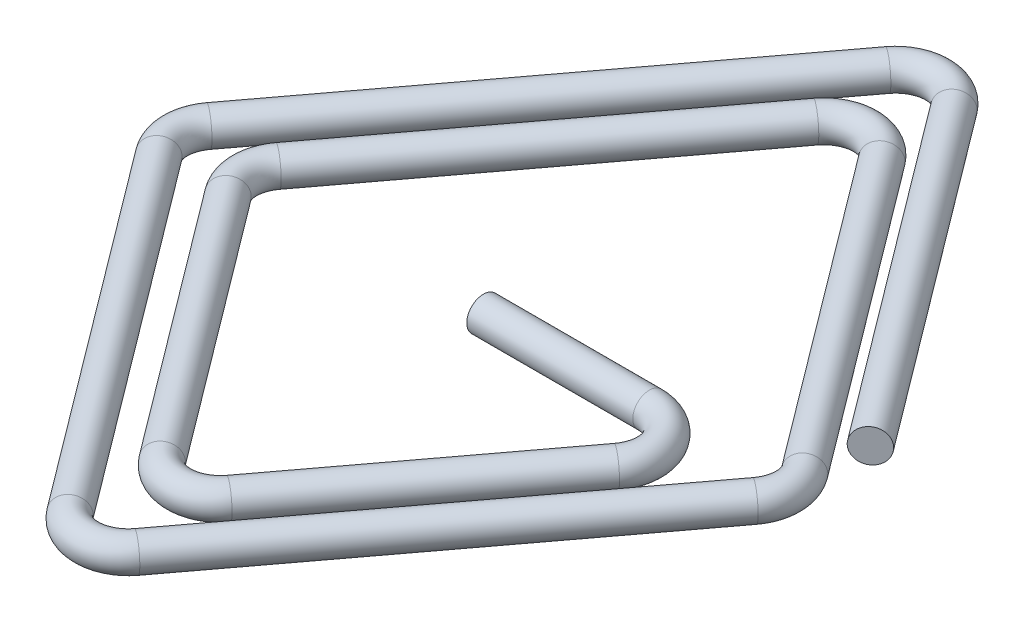
SolidWorks part; units mm, degrees
ref_plane "Спереди" through (0, 0, 0) normal (0, 0, 1) x (1, 0, 0)
ref_plane "Сверху" through (0, 0, 0) normal (0, 1, 0) x (1, 0, 0)
ref_plane "Справа" through (0, 0, 0) normal (1, 0, 0) x (0, 0, -1)
sketch "Эскиз1" plane through (0, 0, 0) normal (0, 1, 0) x (1, 0, 0)
  line L0 (0, 0) -> (9, 0) construction
  line L1 (9, 0) -> (0, -12) construction
  line L2 (0, -12) -> (-9, 0) construction
  line L3 (-9, 0) -> (0, 12) construction
  line L4 (11.45, -0.0667) -> (0, -15.3333) construction
  line L5 (0, -15.3333) -> (-11.5, 0) construction
  line L6 (-11.5, 0) -> (-1.6, 13.2) construction
  line L7 (0, 12) -> (1.2, 13.6) construction
  line L8 (1.2, 13.6) -> (11.45, -0.0667) construction
  line L9 (10.2, 1.6) -> (9, 0) construction
  line L10 (10.6, -1.2) -> (0, -15.3333) construction
  line L12 (2.4, 14.5) -> (12.65, 0.8333) construction
  line L13 (-1.6, 13.2) -> (0.8875, 16.5167) construction
  line L14 (0.8875, 16.5167) -> (2.4, 14.5) construction
  point P16 (11.1375, 2.85)
  dimension "D1" = 12
  dimension "D2" = 9
  dimension "D3" = 2
  dimension "D4" = 2
  dimension "D5" = 1.5
sketch "Эскиз2" plane through (0, 0, 0) normal (0, 1, 0) x (1, 0, 0)
  line L0 (11.1375, 2.85) -> (2.0875, 14.9167)
  line L1 (-0.3125, 14.9167) -> (-10.825, 0.9)
  line L2 (-10.825, -0.9) -> (-1.2, -13.7333)
  line L3 (1.2, -13.7333) -> (10.775, -0.9667)
  line L4 (10.775, 0.8333) -> (2.4, 12)
  line L5 (0, 12) -> (-8.325, 0.9)
  line L6 (-8.325, -0.9) -> (-1.2, -10.4)
  line L7 (1.2, -10.4) -> (7.2, -2.4)
  line L8 (6, 0) -> (0, 0)
  arc A0 (10.775, -0.9667) -> (10.775, 0.8333) centre (9.575, -0.0667) ccw
  arc A1 (-1.2, -10.4) -> (1.2, -10.4) centre (0, -9.5) ccw
  arc A2 (-8.325, -0.9) -> (-8.325, 0.9) centre (-7.125, 0) cw
  arc A3 (2.4, 12) -> (0, 12) centre (1.2, 11.1) ccw
  arc A4 (2.0875, 14.9167) -> (-0.3125, 14.9167) centre (0.8875, 14.0167) ccw
  arc A5 (-10.825, 0.9) -> (-10.825, -0.9) centre (-9.625, 0) ccw
  arc A6 (-1.2, -13.7333) -> (1.2, -13.7333) centre (0, -12.8333) ccw
  arc A7 (6, 0) -> (7.2, -2.4) centre (6, -1.5) cw
  point P22 (11.45, -0.0667)
  point P25 (0, -12)
  point P28 (-9, 0)
  point P31 (1.2, 13.6)
  point P34 (0.8875, 16.5167)
  point P37 (-11.5, 0)
  point P40 (0, -15.3333)
  point P43 (9, 0)
  dimension "D1" = 1.5
  dimension "D2" = 1.5
  dimension "D3" = 1.5
ref_plane "Плоскость3" through (11.1375, 0, -2.85) normal (0.6, 0, 0.8) x (0.8, 0, -0.6)
sketch "Эскиз3" plane through (11.1375, 0, -2.85) normal (0.6, 0, 0.8) x (0.8, 0, -0.6)
  circle A0 centre (0, 0) radius 0.6
  dimension "D1" = 1.2
sweep "По траектории1" add profiles "Эскиз3" path "Эскиз2"
